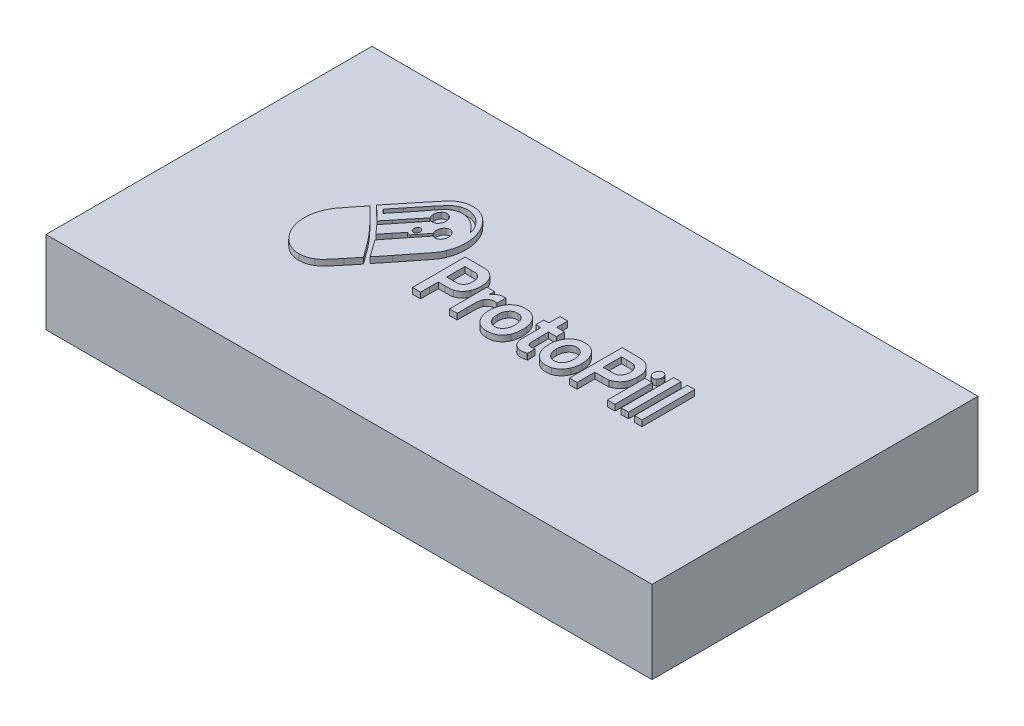
SolidWorks part; units mm, degrees
ref_plane "Front Plane" through (0, 0, 0) normal (0, 0, 1) x (1, 0, 0)
ref_plane "Top Plane" through (0, 0, 0) normal (0, 1, 0) x (1, 0, 0)
ref_plane "Right Plane" through (0, 0, 0) normal (1, 0, 0) x (0, 0, -1)
sketch "Sketch1" plane through (0, 0, 0) normal (0, 1, 0) x (1, 0, 0)
  line L1 (154.1936, -82.9202) -> (-154.1936, -82.9202)
  line L2 (154.1936, -82.9202) -> (154.1936, 82.9202)
  line L3 (154.1936, 82.9202) -> (-154.1936, 82.9202)
  line L4 (-154.1936, -82.9202) -> (-154.1936, 82.9202)
  line L5 (154.1936, -82.9202) -> (-154.1936, 82.9202) construction
  line L6 (154.1936, 82.9202) -> (-154.1936, -82.9202) construction
  point P0 (0, 0)
extrude "Boss-Extrude1" add sketch "Sketch1" along normal blind 42
sketch "Sketch5" plane through (0, 42, 0) normal (0, 1, 0) x (1, 0, 0)
  line L0 (-78.5394, 12.987) -> (-80.0376, 11.138)
  line L1 (-80.0376, 11.138) -> (-78.1265, 9.3031)
  line L2 (-63.4393, 15.8946) -> (-60.7967, 19.0846)
  line L3 (-60.7967, 19.0846) -> (-61.1271, 19.7762)
  line L4 (-58.4019, 17.8425) -> (-59.1452, 17.8425)
  line L5 (-59.1452, 17.8425) -> (-60.667, 15.9229)
  line L6 (-69.9512, 1.0036) -> (-68.571, -0.5349)
  line L7 (-68.571, -0.5349) -> (-65.3622, 3.4031)
  line L8 (-61.7759, 7.8634) -> (-61.3984, 8.3856)
  line L9 (-61.3984, 8.3856) -> (-61.5753, 9.0349)
  line L10 (-72.9241, 4.3347) -> (-71.3197, 2.6127)
  line L11 (-55.5707, 10.0653) -> (-54.4028, 11.5614)
  line L12 (-54.4028, 11.5614) -> (-53.2467, 13.0717)
  line L13 (-53.2467, 13.0717) -> (-53.4944, 13.7633)
  line L14 (-51.6187, 11.6602) -> (-52.0552, 11.8155)
  line L15 (-52.0552, 11.8155) -> (-53.0579, 10.5734)
  line L16 (-72.464, 11.8861) -> (-74.729, 9.0772)
  line L17 (-74.729, 9.0772) -> (-75.6256, 10.0512)
  line L18 (-34.631, -2.6097) -> (-34.631, -16.0187)
  line L19 (-34.631, -16.0187) -> (-32.5665, -16.0187)
  line L20 (-32.5665, -16.0187) -> (-30.502, -16.0187)
  line L21 (-30.502, -16.0187) -> (-30.4785, -11.5302)
  line L22 (-30.4785, -11.5302) -> (-30.4431, -7.0559)
  line L23 (-30.4431, -7.0559) -> (-27.1399, -7.0418)
  line L24 (-29.287, 10.7992) -> (-34.631, 10.7992)
  line L25 (-34.631, 10.7992) -> (-34.631, -2.6097)
  line L26 (-23.7542, -2.2851) -> (-24.4266, -2.6803)
  line L27 (-24.4266, -2.6803) -> (-27.4584, -2.7227)
  line L28 (-27.4584, -2.7227) -> (-30.502, -2.765)
  line L29 (-30.502, -2.765) -> (-30.502, 1.907)
  line L30 (-30.502, 1.907) -> (-30.502, 6.593)
  line L31 (-30.502, 6.593) -> (-27.5174, 6.5366)
  line L32 (45.2347, -2.5956) -> (45.2347, -16.0187)
  line L33 (45.2347, -16.0187) -> (47.1812, -16.0187)
  line L34 (47.1812, -16.0187) -> (49.1277, -16.0187)
  line L35 (49.1277, -16.0187) -> (49.1277, -11.5161)
  line L36 (49.1277, -11.5161) -> (49.1277, -7.0135)
  line L37 (49.1277, -7.0135) -> (52.6432, -6.9571)
  line L38 (52.6432, -6.9571) -> (56.1469, -6.9006)
  line L39 (56.1469, -6.9006) -> (57.2558, -6.4489)
  line L40 (50.5787, 10.771) -> (45.2347, 10.8133)
  line L41 (45.2347, 10.8133) -> (45.2347, -2.5956)
  line L42 (52.2893, -2.7227) -> (49.1277, -2.765)
  line L43 (49.1277, -2.765) -> (49.1277, 1.8929)
  line L44 (49.1277, 1.8929) -> (49.1277, 6.5648)
  line L45 (49.1277, 6.5648) -> (51.7466, 6.5648)
  line L46 (71.9313, 10.6863) -> (71.542, 10.644)
  line L47 (71.542, 10.644) -> (71.542, -2.6944)
  line L48 (71.542, -2.6944) -> (71.542, -16.0328)
  line L49 (71.542, -16.0328) -> (73.4059, -15.9905)
  line L50 (73.4059, -15.9905) -> (75.2581, -15.9481)
  line L51 (75.2581, -15.9481) -> (75.2581, -2.6239)
  line L52 (75.2581, -2.6239) -> (75.2581, 10.7004)
  line L53 (75.2581, 10.7004) -> (73.7834, 10.7145)
  line L54 (78.3843, -2.7085) -> (78.3843, -16.0187)
  line L55 (78.3843, -16.0187) -> (80.2718, -16.0187)
  line L56 (80.2718, -16.0187) -> (82.1593, -16.0187)
  line L57 (82.1593, -16.0187) -> (82.1593, -2.6097)
  line L58 (82.1593, -2.6097) -> (82.1593, 10.8133)
  line L59 (82.1593, 10.8133) -> (80.3426, 10.7851)
  line L60 (-64.7841, -20.606) -> (-60.372, -15.2283)
  line L61 (-60.372, -15.2283) -> (-61.6815, -13.3934)
  line L62 (-84.5323, 1.7094) -> (-81.3117, 5.7462)
  line L63 (-81.3117, 5.7462) -> (-80.3916, 4.6452)
  line L64 (-80.3916, 4.6452) -> (-79.4714, 3.5584)
  line L65 (-79.4714, 3.5584) -> (-80.2028, 2.5986)
  line L66 (15.7186, 5.9014) -> (15.6832, 3.1067)
  line L67 (15.6832, 3.1067) -> (14.4091, 3.0644)
  line L68 (14.4091, 3.0644) -> (13.1351, 3.022)
  line L69 (13.1351, 3.022) -> (13.1704, 1.0177)
  line L70 (13.1704, 1.0177) -> (13.2058, -0.9865)
  line L71 (13.2058, -0.9865) -> (14.4799, -1.0289)
  line L72 (14.4799, -1.0289) -> (15.7422, -1.0712)
  line L73 (15.7422, -1.0712) -> (15.7422, -6.1808)
  line L74 (23.3041, -15.8634) -> (23.717, -15.7082)
  line L75 (23.717, -15.7082) -> (23.6698, -13.7745)
  line L76 (19.6588, -5.8138) -> (19.6234, -1.0571)
  line L77 (19.6234, -1.0571) -> (21.6289, -1.0571)
  line L78 (21.6289, -1.0571) -> (23.6462, -1.0571)
  line L79 (23.6462, -1.0571) -> (23.6462, 0.9895)
  line L80 (23.6462, 0.9895) -> (23.6462, 3.0361)
  line L81 (23.6462, 3.0361) -> (21.6761, 3.0644)
  line L82 (21.6761, 3.0644) -> (19.6942, 3.1067)
  line L83 (19.6942, 3.1067) -> (19.6588, 5.9014)
  line L84 (19.6588, 5.9014) -> (19.6352, 8.682)
  line L85 (19.6352, 8.682) -> (17.6887, 8.682)
  line L86 (17.6887, 8.682) -> (15.7422, 8.682)
  line L87 (15.7422, 8.682) -> (15.7186, 5.9014)
  line L88 (-66.7778, -2.6097) -> (-66.2352, -3.2449)
  line L89 (-66.2352, -3.2449) -> (-64.9729, -1.6923)
  line L90 (-61.0799, 3.1773) -> (-58.4491, 6.4801)
  line L91 (-58.4491, 6.4801) -> (-59.1334, 6.6495)
  line L92 (-11.9808, 1.6952) -> (-11.9808, 3.0361)
  line L93 (-11.9808, 3.0361) -> (-13.8683, 3.0361)
  line L94 (-13.8683, 3.0361) -> (-15.7558, 3.0361)
  line L95 (-15.7558, 3.0361) -> (-15.7558, -6.4913)
  line L96 (-15.7558, -6.4913) -> (-15.7558, -16.0187)
  line L97 (-15.7558, -16.0187) -> (-13.8093, -16.0187)
  line L98 (-13.8093, -16.0187) -> (-11.8628, -16.0187)
  line L99 (-11.8628, -16.0187) -> (-11.8628, -11.0362)
  line L100 (-6.6367, -1.3818) -> (-6.2002, -1.4947)
  line L101 (-6.2002, -1.4947) -> (-6.2002, 0.7778)
  line L102 (-6.2002, 0.7778) -> (-6.2002, 3.0361)
  line L103 (-6.2002, 3.0361) -> (-6.4834, 3.0361)
  line L104 (64.5818, -6.4913) -> (64.5818, -16.0187)
  line L105 (64.5818, -16.0187) -> (66.4693, -16.0187)
  line L106 (66.4693, -16.0187) -> (68.3568, -16.0187)
  line L107 (68.3568, -16.0187) -> (68.3568, -6.4913)
  line L108 (68.3568, -6.4913) -> (68.3568, 3.0361)
  line L109 (68.3568, 3.0361) -> (66.4693, 3.0361)
  line L110 (66.4693, 3.0361) -> (64.5818, 3.0361)
  line L111 (64.5818, 3.0361) -> (64.5818, -6.4913)
  line L112 (-68.571, -0.5349) -> (-67.3087, -1.8899)
  line L113 (-66.2352, -3.2449) -> (-65.0673, -4.6281)
  line L114 (-55.5707, 10.0653) -> (-58.4491, 6.4801)
  line L115 (-59.971, 13.6786) -> (-57.8593, 11.8861)
  spline S0 degree 3 poles (-57.2222, 34.8366) (-59.2277, 34.4131) (-61.5282, 33.2275) (-63.0618, 31.8442) knots 0 0 0 0 1 1 1 1
  spline S1 degree 3 poles (-63.0618, 31.8442) (-63.4865, 31.4632) (-66.8014, 27.4828) (-70.4349, 22.9943) knots 0 0 0 0 1 1 1 1
  spline S2 degree 3 poles (-70.4349, 22.9943) (-74.0684, 18.4917) (-77.7136, 13.9892) (-78.5394, 12.987) knots 0 0 0 0 1 1 1 1
  spline S3 degree 3 poles (-78.1265, 9.3031) (-77.0766, 8.3009) (-75.5076, 6.7624) (-74.6346, 5.8873) knots 0 0 0 0 1 1 1 1
  spline S4 degree 3 poles (-74.6346, 5.8873) (-73.7616, 5.0122) (-72.9948, 4.3206) (-72.9241, 4.3347) knots 0 0 0 0 1 1 1 1
  spline S5 degree 3 poles (-72.9241, 4.3347) (-72.8415, 4.3629) (-71.2843, 6.2543) (-69.4439, 8.5409) knots 0 0 0 0 1 1 1 1
  spline S6 degree 3 poles (-69.4439, 8.5409) (-67.5918, 10.8275) (-64.9021, 14.1444) (-63.4393, 15.8946) knots 0 0 0 0 1 1 1 1
  spline S7 degree 3 poles (-61.1271, 19.7762) (-61.422, 20.3831) (-61.4692, 20.6089) (-61.4692, 21.597) knots 0 0 0 0 1 1 1 1
  spline S8 degree 3 poles (-61.4692, 21.597) (-61.4692, 22.9238) (-61.2332, 23.573) (-60.4664, 24.4058) knots 0 0 0 0 1 1 1 1
  spline S9 degree 3 poles (-60.4664, 24.4058) (-59.8058, 25.1257) (-59.2513, 25.3797) (-58.4019, 25.3797) knots 0 0 0 0 1 1 1 1
  spline S10 degree 3 poles (-58.4019, 25.3797) (-57.5172, 25.3938) (-56.7976, 25.0268) (-56.1369, 24.2223) knots 0 0 0 0 1 1 1 1
  spline S11 degree 3 poles (-56.1369, 24.2223) (-55.4527, 23.3895) (-55.2286, 22.6415) (-55.2993, 21.3147) knots 0 0 0 0 1 1 1 1
  spline S12 degree 3 poles (-55.2993, 21.3147) (-55.3465, 20.4678) (-55.4173, 20.1432) (-55.6886, 19.6774) knots 0 0 0 0 1 1 1 1
  spline S13 degree 3 poles (-55.6886, 19.6774) (-56.3965, 18.3788) (-57.2105, 17.8284) (-58.4019, 17.8425) knots 0 0 0 0 1 1 1 1
  spline S14 degree 3 poles (-60.667, 15.9229) (-61.4928, 14.8643) (-64.2297, 11.4485) (-66.7424, 8.3433) knots 0 0 0 0 1 1 1 1
  spline S15 degree 3 poles (-66.7424, 8.3433) (-69.267, 5.238) (-71.3197, 2.655) (-71.3197, 2.6127) knots 0 0 0 0 1 1 1 1
  spline S16 degree 3 poles (-71.3197, 2.6127) (-71.3197, 2.5562) (-70.7062, 1.8364) (-69.9512, 1.0036) knots 0 0 0 0 1 1 1 1
  spline S17 degree 3 poles (-65.3622, 3.4031) (-63.6044, 5.5768) (-61.9882, 7.5811) (-61.7759, 7.8634) knots 0 0 0 0 1 1 1 1
  spline S18 degree 3 poles (-61.5753, 9.0349) (-62.0944, 10.8416) (-61.4102, 12.8176) (-59.971, 13.6786) knots 0 0 0 0 1 1 1 1
  spline S20 degree 3 poles (-53.4944, 13.7633) (-54.1432, 15.57) (-53.5416, 17.6731) (-52.1024, 18.6047) knots 0 0 0 0 1 1 1 1
  spline S21 degree 3 poles (-52.1024, 18.6047) (-50.8755, 19.4092) (-49.5778, 19.1975) (-48.5279, 18.0401) knots 0 0 0 0 1 1 1 1
  spline S22 degree 3 poles (-48.5279, 18.0401) (-46.8645, 16.1628) (-47.3953, 12.7894) (-49.5424, 11.7167) knots 0 0 0 0 1 1 1 1
  spline S23 degree 3 poles (-49.5424, 11.7167) (-50.0379, 11.4626) (-51.0052, 11.4485) (-51.6187, 11.6602) knots 0 0 0 0 1 1 1 1
  spline S24 degree 3 poles (-53.0579, 10.5734) (-53.9663, 9.4301) (-57.4936, 4.984) (-62.9674, -1.8899) knots 0 0 0 0 1 1 1 1
  spline S25 degree 3 poles (-62.9674, -1.8899) (-64.1235, -3.3296) (-65.0673, -4.5717) (-65.0673, -4.6281) knots 0 0 0 0 1 1 1 1
  spline S26 degree 3 poles (-65.0673, -4.6281) (-65.0673, -4.6987) (-64.3594, -5.715) (-63.4983, -6.8865) knots 0 0 0 0 1 1 1 1
  spline S27 degree 3 poles (-63.4983, -6.8865) (-62.6371, -8.0721) (-61.2686, -9.9494) (-60.4782, -11.0786) knots 0 0 0 0 1 1 1 1
  spline S28 degree 3 poles (-60.4782, -11.0786) (-59.676, -12.2077) (-58.98, -13.1675) (-58.9446, -13.224) knots 0 0 0 0 1 1 1 1
  spline S29 degree 3 poles (-58.9446, -13.224) (-58.8974, -13.2946) (-56.5734, -10.4575) (-53.7893, -6.9429) knots 0 0 0 0 1 1 1 1
  spline S30 degree 3 poles (-53.7893, -6.9429) (-42.9833, 6.6354) (-43.349, 6.1273) (-42.1929, 8.922) knots 0 0 0 0 1 1 1 1
  spline S31 degree 3 poles (-42.1929, 8.922) (-39.7037, 14.8925) (-40.0694, 21.6534) (-43.1956, 27.4122) knots 0 0 0 0 1 1 1 1
  spline S32 degree 3 poles (-43.1956, 27.4122) (-44.3635, 29.5718) (-46.5696, 31.9854) (-48.4453, 33.171) knots 0 0 0 0 1 1 1 1
  spline S33 degree 3 poles (-48.4453, 33.171) (-49.4834, 33.8203) (-51.4299, 34.5825) (-52.7276, 34.8648) knots 0 0 0 0 1 1 1 1
  spline S34 degree 3 poles (-52.7276, 34.8648) (-54.0017, 35.1189) (-55.9482, 35.1189) (-57.2222, 34.8366) knots 0 0 0 0 1 1 1 1
  spline S35 degree 3 poles (-52.2675, 31.9007) (-49.7194, 31.2655) (-47.4425, 29.5577) (-45.6966, 26.9323) knots 0 0 0 0 1 1 1 1
  spline S36 degree 3 poles (-45.6966, 26.9323) (-44.7646, 25.535) (-43.7855, 23.079) (-44.1512, 23.079) knots 0 0 0 0 1 1 1 1
  spline S37 degree 3 poles (-44.1512, 23.079) (-44.1984, 23.079) (-44.7174, 23.6718) (-45.3191, 24.4058) knots 0 0 0 0 1 1 1 1
  spline S38 degree 3 poles (-45.3191, 24.4058) (-48.575, 28.3579) (-53.0579, 30.0799) (-56.9863, 28.866) knots 0 0 0 0 1 1 1 1
  spline S39 degree 3 poles (-56.9863, 28.866) (-58.2368, 28.4849) (-59.8884, 27.4969) (-60.8439, 26.5371) knots 0 0 0 0 1 1 1 1
  spline S40 degree 3 poles (-60.8439, 26.5371) (-61.2804, 26.1137) (-62.5309, 24.5469) (-63.628, 23.0508) knots 0 0 0 0 1 1 1 1
  spline S41 degree 3 poles (-63.628, 23.0508) (-65.4919, 20.5101) (-66.6127, 19.0987) (-72.464, 11.8861) knots 0 0 0 0 1 1 1 1
  spline S42 degree 3 poles (-75.6256, 10.0512) (-76.1092, 10.5734) (-76.5103, 11.0392) (-76.5103, 11.0815) knots 0 0 0 0 1 1 1 1
  spline S43 degree 3 poles (-76.5103, 11.0815) (-76.5103, 11.1239) (-74.4813, 13.6504) (-71.9921, 16.6709) knots 0 0 0 0 1 1 1 1
  spline S44 degree 3 poles (-71.9921, 16.6709) (-69.5147, 19.7056) (-66.3177, 23.6295) (-64.8903, 25.3938) knots 0 0 0 0 1 1 1 1
  spline S45 degree 3 poles (-64.8903, 25.3938) (-61.5635, 29.5153) (-60.5372, 30.461) (-58.343, 31.4208) knots 0 0 0 0 1 1 1 1
  spline S46 degree 3 poles (-58.343, 31.4208) (-56.4201, 32.2536) (-54.391, 32.4229) (-52.2675, 31.9007) knots 0 0 0 0 1 1 1 1
  spline S47 degree 3 poles (-59.2631, 23.2202) (-60.2187, 22.5144) (-60.2069, 20.6936) (-59.2277, 19.9738) knots 0 0 0 0 1 1 1 1
  spline S48 degree 3 poles (-59.2277, 19.9738) (-58.166, 19.1975) (-56.8094, 20.1008) (-56.8094, 21.597) knots 0 0 0 0 1 1 1 1
  spline S49 degree 3 poles (-56.8094, 21.597) (-56.8094, 23.0931) (-58.1778, 24.0106) (-59.2631, 23.2202) knots 0 0 0 0 1 1 1 1
  spline S50 degree 3 poles (-51.3355, 17.0097) (-51.4653, 16.9532) (-51.7248, 16.6992) (-51.89, 16.4451) knots 0 0 0 0 1 1 1 1
  spline S51 degree 3 poles (-51.89, 16.4451) (-52.1377, 16.1064) (-52.2085, 15.8523) (-52.2085, 15.3442) knots 0 0 0 0 1 1 1 1
  spline S52 degree 3 poles (-52.2085, 15.3442) (-52.2085, 14.5114) (-52.0198, 14.0738) (-51.5125, 13.6645) knots 0 0 0 0 1 1 1 1
  spline S53 degree 3 poles (-51.5125, 13.6645) (-50.5216, 12.86) (-49.1295, 13.721) (-49.0941, 15.1466) knots 0 0 0 0 1 1 1 1
  spline S54 degree 3 poles (-49.0941, 15.1466) (-49.0823, 15.8946) (-49.3419, 16.5439) (-49.7901, 16.8686) knots 0 0 0 0 1 1 1 1
  spline S55 degree 3 poles (-49.7901, 16.8686) (-50.1794, 17.165) (-50.8873, 17.2214) (-51.3355, 17.0097) knots 0 0 0 0 1 1 1 1
  spline S56 degree 3 poles (-59.4873, 11.9284) (-60.5372, 11.1662) (-60.4546, 9.2466) (-59.3457, 8.6256) knots 0 0 0 0 1 1 1 1
  spline S57 degree 3 poles (-59.3457, 8.6256) (-58.3312, 8.0469) (-57.1633, 8.9502) (-57.1633, 10.3052) knots 0 0 0 0 1 1 1 1
  spline S58 degree 3 poles (-57.1633, 10.3052) (-57.1633, 11.0392) (-57.3638, 11.4908) (-57.8593, 11.8861) knots 0 0 0 0 1 1 1 1
  spline S59 degree 3 poles (-57.8593, 11.8861) (-58.3548, 12.2813) (-58.98, 12.3095) (-59.4873, 11.9284) knots 0 0 0 0 1 1 1 1
  spline S60 degree 3 poles (-27.1399, -7.0418) (-24.1671, -7.0276) (-23.7424, -6.9994) (-22.9166, -6.7312) knots 0 0 0 0 1 1 1 1
  spline S61 degree 3 poles (-22.9166, -6.7312) (-20.8875, -6.0678) (-19.3539, -4.5999) (-18.4809, -2.4686) knots 0 0 0 0 1 1 1 1
  spline S62 degree 3 poles (-18.4809, -2.4686) (-17.8203, -0.8454) (-17.6079, 0.439) (-17.6787, 2.401) knots 0 0 0 0 1 1 1 1
  spline S63 degree 3 poles (-17.6787, 2.401) (-17.8085, 5.9155) (-19.1297, 8.4985) (-21.4773, 9.8959) knots 0 0 0 0 1 1 1 1
  spline S64 degree 3 poles (-21.4773, 9.8959) (-22.9284, 10.7428) (-23.3413, 10.7992) (-29.287, 10.7992) knots 0 0 0 0 1 1 1 1
  spline S65 degree 3 poles (-24.0019, 6.2261) (-23.2587, 5.9014) (-22.5391, 5.1251) (-22.1498, 4.25) knots 0 0 0 0 1 1 1 1
  spline S66 degree 3 poles (-22.1498, 4.25) (-21.8548, 3.6007) (-21.8312, 3.389) (-21.8312, 1.9775) knots 0 0 0 0 1 1 1 1
  spline S67 degree 3 poles (-21.8312, 1.9775) (-21.8312, 0.6931) (-21.8784, 0.312) (-22.079, -0.2244) knots 0 0 0 0 1 1 1 1
  spline S68 degree 3 poles (-22.079, -0.2244) (-22.4447, -1.1559) (-22.9992, -1.8334) (-23.7542, -2.2851) knots 0 0 0 0 1 1 1 1
  spline S69 degree 3 poles (-27.5174, 6.5366) (-25.0518, 6.4801) (-24.4502, 6.4378) (-24.0019, 6.2261) knots 0 0 0 0 1 1 1 1
  spline S70 degree 3 poles (57.2558, -6.4489) (60.4646, -5.1222) (62.1516, -2.2145) (62.1516, 1.9775) knots 0 0 0 0 1 1 1 1
  spline S71 degree 3 poles (62.1516, 1.9775) (62.1516, 4.6311) (61.491, 6.593) (60.0517, 8.2304) knots 0 0 0 0 1 1 1 1
  spline S72 degree 3 poles (60.0517, 8.2304) (59.0726, 9.3313) (58.117, 9.9806) (56.8311, 10.404) knots 0 0 0 0 1 1 1 1
  spline S73 degree 3 poles (56.8311, 10.404) (55.9582, 10.7004) (55.6043, 10.7145) (50.5787, 10.771) knots 0 0 0 0 1 1 1 1
  spline S74 degree 3 poles (55.097, 6.4096) (56.5716, 6.099) (57.6687, 4.9134) (58.0344, 3.2479) knots 0 0 0 0 1 1 1 1
  spline S75 degree 3 poles (58.0344, 3.2479) (58.2704, 2.1187) (58.2586, 1.413) (57.9637, 0.2838) knots 0 0 0 0 1 1 1 1
  spline S76 degree 3 poles (57.9637, 0.2838) (57.6687, -0.8877) (56.9609, -1.8617) (56.0525, -2.3416) knots 0 0 0 0 1 1 1 1
  spline S77 degree 3 poles (56.0525, -2.3416) (55.4627, -2.6662) (55.2975, -2.6803) (52.2893, -2.7227) knots 0 0 0 0 1 1 1 1
  spline S78 degree 3 poles (51.7466, 6.5648) (53.1859, 6.5648) (54.6959, 6.4942) (55.097, 6.4096) knots 0 0 0 0 1 1 1 1
  spline S79 degree 3 poles (73.7834, 10.7145) (72.9694, 10.7287) (72.1319, 10.7145) (71.9313, 10.6863) knots 0 0 0 0 1 1 1 1
  spline S80 degree 3 poles (78.455, 10.6863) (78.4197, 10.644) (78.3843, 4.617) (78.3843, -2.7085) knots 0 0 0 0 1 1 1 1
  spline S81 degree 3 poles (80.3426, 10.7851) (79.3398, 10.7851) (78.4904, 10.7428) (78.455, 10.6863) knots 0 0 0 0 1 1 1 1
  spline S82 degree 3 poles (65.6435, 10.2205) (64.452, 9.6559) (63.9329, 7.7787) (64.6054, 6.4096) knots 0 0 0 0 1 1 1 1
  spline S83 degree 3 poles (64.6054, 6.4096) (65.0537, 5.4921) (65.6907, 5.111) (66.6463, 5.1816) knots 0 0 0 0 1 1 1 1
  spline S84 degree 3 poles (66.6463, 5.1816) (67.2715, 5.2239) (67.4838, 5.3086) (67.8495, 5.6615) knots 0 0 0 0 1 1 1 1
  spline S85 degree 3 poles (67.8495, 5.6615) (68.4276, 6.212) (68.7107, 6.8895) (68.7107, 7.7222) knots 0 0 0 0 1 1 1 1
  spline S86 degree 3 poles (68.7107, 7.7222) (68.7107, 8.8655) (68.2506, 9.7689) (67.4484, 10.1782) knots 0 0 0 0 1 1 1 1
  spline S87 degree 3 poles (67.4484, 10.1782) (67.012, 10.404) (66.08, 10.4181) (65.6435, 10.2205) knots 0 0 0 0 1 1 1 1
  spline S88 degree 3 poles (-85.075, 4.5041) (-87.0805, 1.9634) (-88.9444, -0.4361) (-89.2275, -0.8313) knots 0 0 0 0 1 1 1 1
  spline S89 degree 3 poles (-89.2275, -0.8313) (-90.4308, -2.5392) (-91.6341, -5.1927) (-92.2593, -7.4793) knots 0 0 0 0 1 1 1 1
  spline S90 degree 3 poles (-92.2593, -7.4793) (-93.1441, -10.7539) (-93.1205, -14.7201) (-92.2004, -18.023) knots 0 0 0 0 1 1 1 1
  spline S91 degree 3 poles (-92.2004, -18.023) (-91.4925, -20.5636) (-90.4662, -22.5679) (-88.8618, -24.5722) knots 0 0 0 0 1 1 1 1
  spline S92 degree 3 poles (-88.8618, -24.5722) (-85.9008, -28.2844) (-82.4914, -30.0487) (-78.3389, -30.0346) knots 0 0 0 0 1 1 1 1
  spline S93 degree 3 poles (-78.3389, -30.0346) (-75.9913, -30.0205) (-74.1745, -29.4982) (-72.0747, -28.2138) knots 0 0 0 0 1 1 1 1
  spline S94 degree 3 poles (-72.0747, -28.2138) (-70.1754, -27.0564) (-69.4203, -26.266) (-64.7841, -20.606) knots 0 0 0 0 1 1 1 1
  spline S95 degree 3 poles (-61.6815, -13.3934) (-66.0582, -7.2676) (-68.1463, -4.6281) (-71.6736, -0.7748) knots 0 0 0 0 1 1 1 1
  spline S96 degree 3 poles (-71.6736, -0.7748) (-74.7526, 2.5986) (-80.9342, 8.8937) (-81.3471, 9.0772) knots 0 0 0 0 1 1 1 1
  spline S97 degree 3 poles (-81.3471, 9.0772) (-81.3943, 9.0914) (-83.0695, 7.0447) (-85.075, 4.5041) knots 0 0 0 0 1 1 1 1
  spline S98 degree 3 poles (-80.2028, 2.5986) (-80.6039, 2.0763) (-81.8426, 0.4814) (-82.9633, -0.9442) knots 0 0 0 0 1 1 1 1
  spline S99 degree 3 poles (-82.9633, -0.9442) (-84.0722, -2.3698) (-85.3581, -4.0635) (-85.8064, -4.7128) knots 0 0 0 0 1 1 1 1
  spline S100 degree 3 poles (-85.8064, -4.7128) (-87.8001, -7.5922) (-88.8736, -10.7116) (-89.0977, -14.3249) knots 0 0 0 0 1 1 1 1
  spline S101 degree 3 poles (-89.0977, -14.3249) (-89.1921, -15.7646) (-89.2039, -15.807) (-89.4752, -15.807) knots 0 0 0 0 1 1 1 1
  spline S102 degree 3 poles (-89.4752, -15.807) (-89.723, -15.807) (-89.8174, -15.6799) (-90.0297, -15.0307) knots 0 0 0 0 1 1 1 1
  spline S103 degree 3 poles (-90.0297, -15.0307) (-90.3954, -13.9438) (-90.6667, -12.2642) (-90.6667, -11.1068) knots 0 0 0 0 1 1 1 1
  spline S104 degree 3 poles (-90.6667, -11.1068) (-90.6667, -9.1872) (-90.1005, -6.6183) (-89.3101, -4.9245) knots 0 0 0 0 1 1 1 1
  spline S105 degree 3 poles (-89.3101, -4.9245) (-88.6731, -3.5836) (-88.0478, -2.6944) (-84.5323, 1.7094) knots 0 0 0 0 1 1 1 1
  spline S106 degree 3 poles (15.7422, -6.1808) (15.7422, -10.7116) (15.7658, -11.4032) (15.9545, -12.236) knots 0 0 0 0 1 1 1 1
  spline S107 degree 3 poles (15.9545, -12.236) (16.4972, -14.5649) (17.7477, -15.8211) (19.8711, -16.1881) knots 0 0 0 0 1 1 1 1
  spline S108 degree 3 poles (19.8711, -16.1881) (20.8739, -16.3575) (22.3603, -16.2163) (23.3041, -15.8634) knots 0 0 0 0 1 1 1 1
  spline S109 degree 3 poles (23.6698, -13.7745) (23.6462, -12.7159) (23.6108, -11.8407) (23.5872, -11.8125) knots 0 0 0 0 1 1 1 1
  spline S110 degree 3 poles (23.5872, -11.8125) (23.5754, -11.7984) (23.2569, -11.869) (22.8676, -11.996) knots 0 0 0 0 1 1 1 1
  spline S111 degree 3 poles (22.8676, -11.996) (21.4873, -12.4195) (20.4964, -12.123) (19.9773, -11.135) knots 0 0 0 0 1 1 1 1
  spline S112 degree 3 poles (19.9773, -11.135) (19.6942, -10.5845) (19.6942, -10.5704) (19.6588, -5.8138) knots 0 0 0 0 1 1 1 1
  spline S113 degree 3 poles (-63.7578, 2.6127) (-65.7043, 0.185) (-67.3087, -1.8334) (-67.3087, -1.8899) knots 0 0 0 0 1 1 1 1
  spline S114 degree 3 poles (-67.3087, -1.8899) (-67.3087, -1.9463) (-67.0727, -2.271) (-66.7778, -2.6097) knots 0 0 0 0 1 1 1 1
  spline S115 degree 3 poles (-64.9729, -1.6923) (-64.2769, -0.8313) (-62.5191, 1.3565) (-61.0799, 3.1773) knots 0 0 0 0 1 1 1 1
  spline S116 degree 3 poles (-59.1334, 6.6495) (-59.5109, 6.7483) (-59.9002, 6.8612) (-60.0063, 6.9177) knots 0 0 0 0 1 1 1 1
  spline S117 degree 3 poles (-60.0063, 6.9177) (-60.1479, 6.9741) (-61.1389, 5.845) (-63.7578, 2.6127) knots 0 0 0 0 1 1 1 1
  spline S118 degree 3 poles (1.397, 3.262) (-1.505, 2.4716) (-3.5695, 0.3261) (-4.4897, -2.8497) knots 0 0 0 0 1 1 1 1
  spline S119 degree 3 poles (-4.4897, -2.8497) (-5.9407, -7.8322) (-4.3009, -13.1958) (-0.691, -15.313) knots 0 0 0 0 1 1 1 1
  spline S120 degree 3 poles (-0.691, -15.313) (0.5948, -16.061) (1.6684, -16.3292) (3.4143, -16.3292) knots 0 0 0 0 1 1 1 1
  spline S121 degree 3 poles (3.4143, -16.3292) (7.036, -16.3433) (9.5724, -14.7343) (11.0116, -11.5161) knots 0 0 0 0 1 1 1 1
  spline S122 degree 3 poles (11.0116, -11.5161) (11.8374, -9.653) (12.1559, -6.8583) (11.802, -4.4729) knots 0 0 0 0 1 1 1 1
  spline S123 degree 3 poles (11.802, -4.4729) (11.2593, -0.7325) (9.4662, 1.7799) (6.5169, 2.9656) knots 0 0 0 0 1 1 1 1
  spline S124 degree 3 poles (6.5169, 2.9656) (5.6676, 3.3043) (5.3136, 3.3608) (3.8272, 3.4031) knots 0 0 0 0 1 1 1 1
  spline S125 degree 3 poles (3.8272, 3.4031) (2.6475, 3.4455) (1.8925, 3.389) (1.397, 3.262) knots 0 0 0 0 1 1 1 1
  spline S126 degree 3 poles (5.5024, -1.0853) (6.8237, -1.8193) (7.5905, -3.1179) (7.9326, -5.2068) knots 0 0 0 0 1 1 1 1
  spline S127 degree 3 poles (7.9326, -5.2068) (8.2865, -7.3664) (7.732, -9.7235) (6.5641, -10.9374) knots 0 0 0 0 1 1 1 1
  spline S128 degree 3 poles (6.5641, -10.9374) (5.9035, -11.6431) (5.5024, -11.9113) (4.712, -12.1513) knots 0 0 0 0 1 1 1 1
  spline S129 degree 3 poles (4.712, -12.1513) (2.8363, -12.7582) (0.8426, -11.9113) (-0.1838, -10.0623) knots 0 0 0 0 1 1 1 1
  spline S130 degree 3 poles (-0.1838, -10.0623) (-0.809, -8.9331) (-1.0567, -7.9027) (-1.0567, -6.4207) knots 0 0 0 0 1 1 1 1
  spline S131 degree 3 poles (-1.0567, -6.4207) (-1.0567, -4.6705) (-0.7146, -3.4284) (0.064, -2.4121) knots 0 0 0 0 1 1 1 1
  spline S132 degree 3 poles (0.064, -2.4121) (1.1493, -0.9865) (1.9043, -0.6196) (3.6503, -0.676) knots 0 0 0 0 1 1 1 1
  spline S133 degree 3 poles (3.6503, -0.676) (4.6412, -0.7043) (4.9361, -0.7607) (5.5024, -1.0853) knots 0 0 0 0 1 1 1 1
  spline S134 degree 3 poles (31.4912, 3.2338) (30.5002, 2.9656) (29.2498, 2.3586) (28.5655, 1.7799) knots 0 0 0 0 1 1 1 1
  spline S135 degree 3 poles (28.5655, 1.7799) (27.0555, 0.5378) (25.7578, -1.8193) (25.345, -4.0777) knots 0 0 0 0 1 1 1 1
  spline S136 degree 3 poles (25.345, -4.0777) (25.0618, -5.6726) (25.1562, -8.1992) (25.5691, -9.7377) knots 0 0 0 0 1 1 1 1
  spline S137 degree 3 poles (25.5691, -9.7377) (26.4539, -12.9982) (28.5537, -15.2989) (31.4086, -16.1034) knots 0 0 0 0 1 1 1 1
  spline S138 degree 3 poles (31.4086, -16.1034) (32.5765, -16.4421) (34.8887, -16.3998) (36.0684, -16.0328) knots 0 0 0 0 1 1 1 1
  spline S139 degree 3 poles (36.0684, -16.0328) (38.3688, -15.313) (40.162, -13.6192) (41.1529, -11.2056) knots 0 0 0 0 1 1 1 1
  spline S140 degree 3 poles (41.1529, -11.2056) (41.8018, -9.6247) (42.0495, -8.3826) (42.0495, -6.5336) knots 0 0 0 0 1 1 1 1
  spline S141 degree 3 poles (42.0495, -6.5336) (42.0495, -4.6846) (41.8018, -3.3578) (41.1529, -1.777) knots 0 0 0 0 1 1 1 1
  spline S142 degree 3 poles (41.1529, -1.777) (40.7164, -0.7184) (40.4215, -0.2244) (39.7019, 0.6366) knots 0 0 0 0 1 1 1 1
  spline S143 degree 3 poles (39.7019, 0.6366) (38.6874, 1.8646) (37.9324, 2.4292) (36.5639, 2.9797) knots 0 0 0 0 1 1 1 1
  spline S144 degree 3 poles (36.5639, 2.9797) (35.7617, 3.3043) (35.3842, 3.3608) (33.9686, 3.4031) knots 0 0 0 0 1 1 1 1
  spline S145 degree 3 poles (33.9686, 3.4031) (32.7771, 3.4455) (32.0928, 3.389) (31.4912, 3.2338) knots 0 0 0 0 1 1 1 1
  spline S146 degree 3 poles (34.4404, -0.6478) (36.7644, -1.1559) (38.1565, -3.386) (38.1565, -6.576) knots 0 0 0 0 1 1 1 1
  spline S147 degree 3 poles (38.1565, -6.576) (38.1565, -10.147) (36.0802, -12.5606) (33.2371, -12.3065) knots 0 0 0 0 1 1 1 1
  spline S148 degree 3 poles (33.2371, -12.3065) (30.7834, -12.0807) (29.0728, -9.6953) (29.0728, -6.5054) knots 0 0 0 0 1 1 1 1
  spline S149 degree 3 poles (29.0728, -6.5054) (29.0728, -3.0191) (30.7598, -0.7607) (33.5675, -0.5066) knots 0 0 0 0 1 1 1 1
  spline S150 degree 3 poles (33.5675, -0.5066) (33.6618, -0.5066) (34.0629, -0.5631) (34.4404, -0.6478) knots 0 0 0 0 1 1 1 1
  spline S151 degree 3 poles (-7.8518, 3.0361) (-9.2321, 2.8385) (-10.5297, 2.0905) (-11.3673, 1.0036) knots 0 0 0 0 1 1 1 1
  spline S152 degree 3 poles (-11.3673, 1.0036) (-11.6386, 0.6508) (-11.8982, 0.3544) (-11.9218, 0.3544) knots 0 0 0 0 1 1 1 1
  spline S153 degree 3 poles (-11.9218, 0.3544) (-11.9572, 0.3544) (-11.9808, 0.9613) (-11.9808, 1.6952) knots 0 0 0 0 1 1 1 1
  spline S154 degree 3 poles (-11.8628, -11.0362) (-11.8628, -5.6303) (-11.7802, -4.6564) (-11.2139, -3.5272) knots 0 0 0 0 1 1 1 1
  spline S155 degree 3 poles (-11.2139, -3.5272) (-10.4, -1.8475) (-8.4417, -0.9301) (-6.6367, -1.3818) knots 0 0 0 0 1 1 1 1
  spline S156 degree 3 poles (-6.4834, 3.0361) (-6.6367, 3.0361) (-6.8373, 3.0644) (-6.9316, 3.0926) knots 0 0 0 0 1 1 1 1
  spline S157 degree 3 poles (-6.9316, 3.0926) (-7.0142, 3.1208) (-7.4271, 3.0926) (-7.8518, 3.0361) knots 0 0 0 0 1 1 1 1
extrude "Boss-Extrude2" add sketch "Sketch5" along normal blind 3
